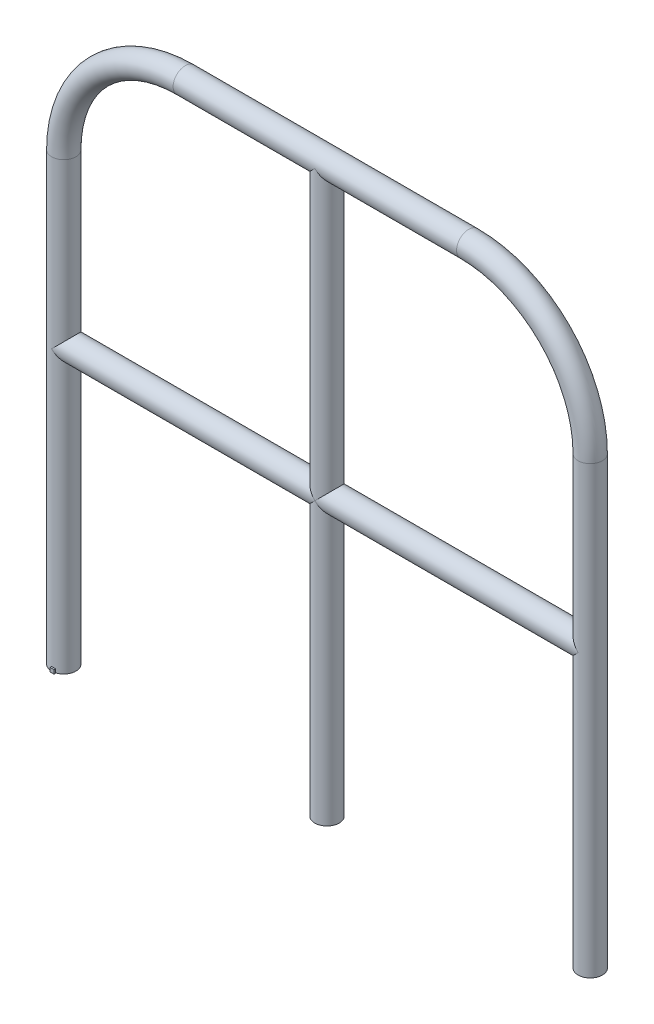
SolidWorks part; units mm, degrees
ref_plane "前视基准面" through (0, 0, 0) normal (0, 0, 1) x (1, 0, 0)
ref_plane "上视基准面" through (0, 0, 0) normal (0, 1, 0) x (1, 0, 0)
ref_plane "右视基准面" through (0, 0, 0) normal (1, 0, 0) x (0, 0, -1)
sketch "草图1" plane through (0, 0, 0) normal (0, 0, 1) x (1, 0, 0)
  line L0 (0, 0) -> (0, 1100)
  line L1 (300, 1400) -> (1000, 1400)
  line L2 (1300, 1100) -> (1300, 0)
  arc A0 (1300, 1100) -> (1000, 1400) centre (1000, 1100) ccw
  arc A1 (0, 1100) -> (300, 1400) centre (300, 1100) cw
  dimension "D1" = 300
sketch "草图2" plane through (0, 0, 0) normal (0, 1, 0) x (1, 0, 0)
  circle A0 centre (0, 0) radius 30
  dimension "D1" = 60
sweep "扫描1" add profiles "草图2" path "草图1"
sketch "草图4" plane through (0, 0, 0) normal (0, 1, 0) x (1, 0, 0)
  circle A0 centre (650, 0) radius 30
extrude "凸台-拉伸1" add sketch "草图4" along normal blind 1400
sketch "草图5" plane through (0, 0, 0) normal (1, 0, 0) x (0, 0, -1)
  circle A0 centre (0, 689.391) radius 30
extrude "凸台-拉伸2" add sketch "草图5" along normal blind 1300
sketch "草图6" plane through (0, 0, 0) normal (0, -1, 0) x (1, 0, 0)
  line L1 (0, 30) -> (9.7571, 30)
  line L2 (0, 30) -> (0, 33.6166)
  line L3 (0, 33.6166) -> (9.7571, 33.6166)
  line L4 (9.7571, 30) -> (9.7571, 33.6166)
  circle A0 centre (0, 0) radius 30 construction
extrude "凸台-拉伸3" add sketch "草图6" against normal blind 10 separate body
